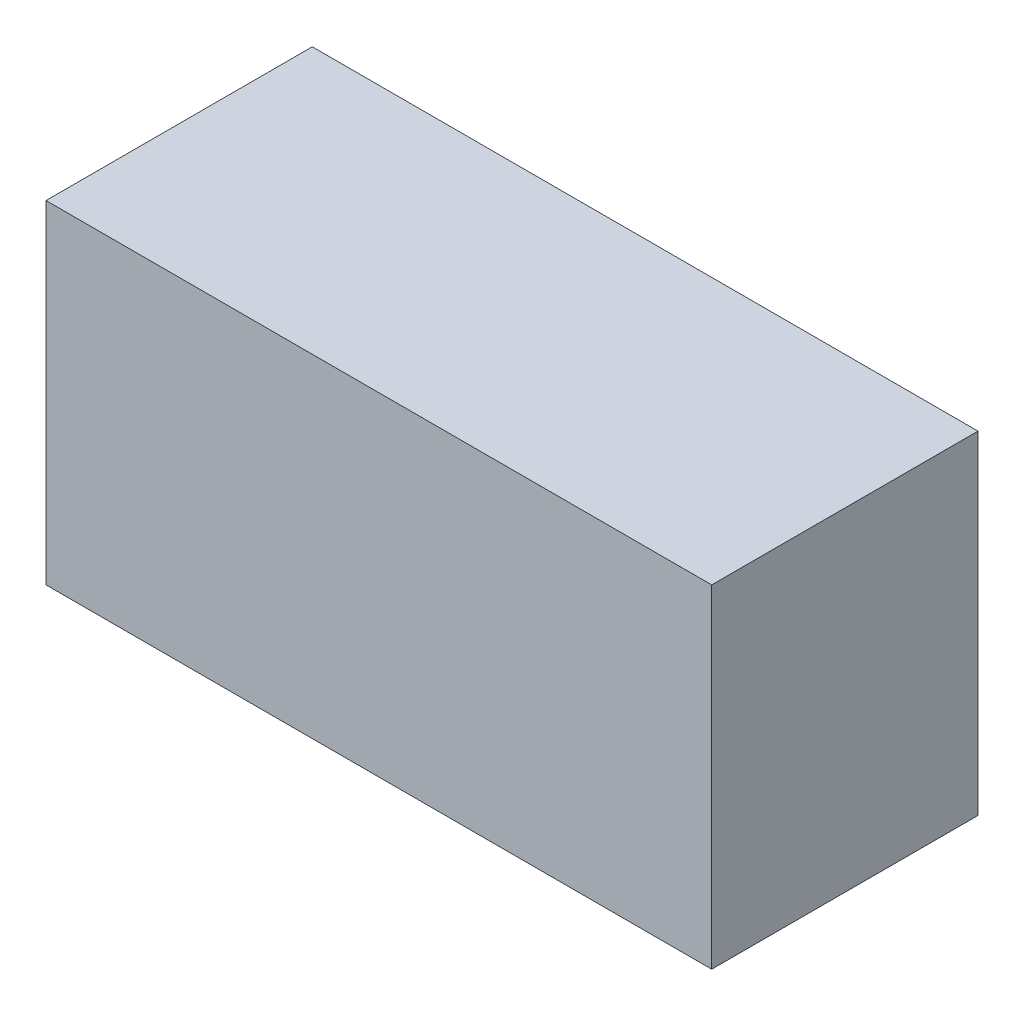
SolidWorks part; units mm, degrees
ref_plane "Płaszczyzna przednia" through (0, 0, 0) normal (0, 0, 1) x (1, 0, 0)
ref_plane "Płaszczyzna górna" through (0, 0, 0) normal (0, 1, 0) x (1, 0, 0)
ref_plane "Płaszczyzna prawa" through (0, 0, 0) normal (1, 0, 0) x (0, 0, -1)
sketch "Sketch1" plane through (0, 0, 0) normal (0, 0, 1) x (1, 0, 0)
  line L1 (-14.0357, 3.9821) -> (5.9643, 3.9821)
  line L2 (-14.0357, 3.9821) -> (-14.0357, -6.0179)
  line L3 (-14.0357, -6.0179) -> (5.9643, -6.0179)
  line L4 (5.9643, 3.9821) -> (5.9643, -6.0179)
  dimension "D1" = 20
  dimension "D2" = 10
extrude "Boss-Extrude1" add sketch "Sketch1" along normal blind 8
